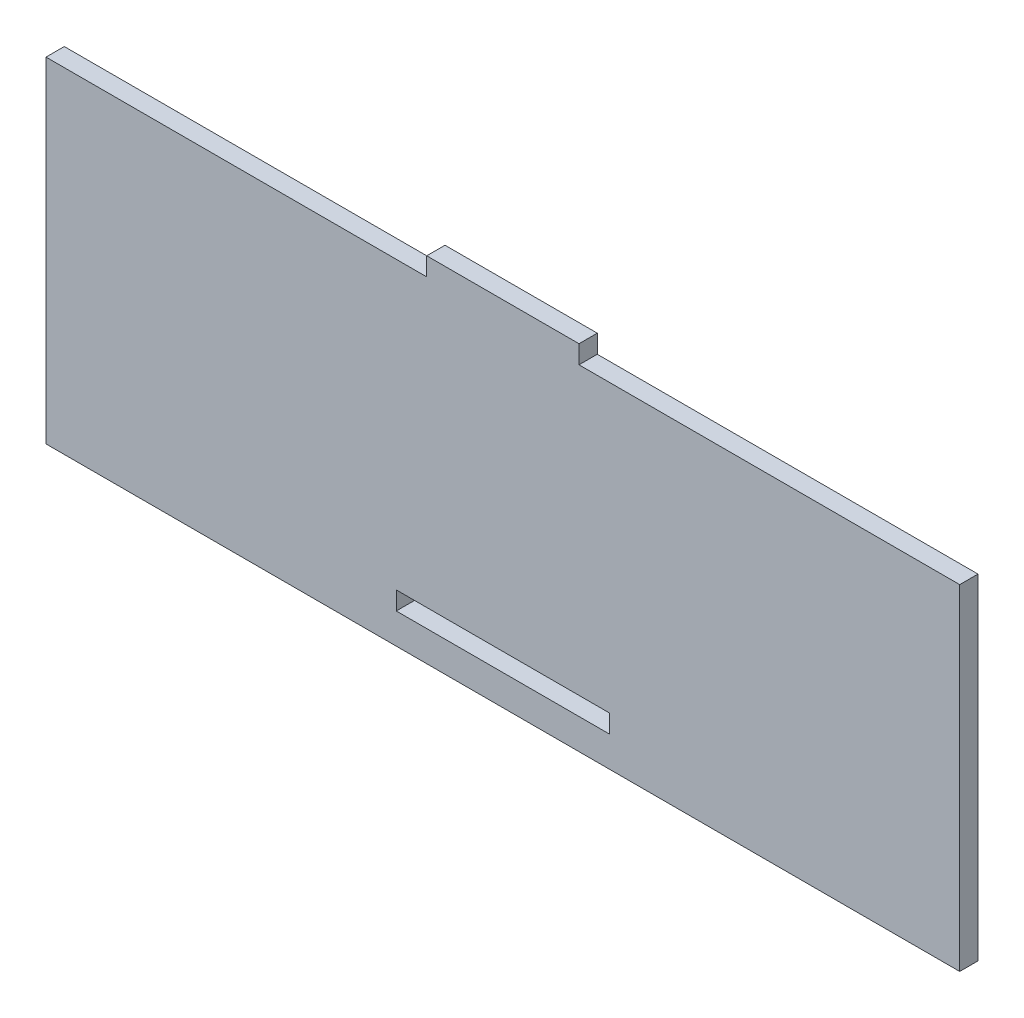
SolidWorks part; units mm, degrees
ref_plane "Спереди" through (0, 0, 0) normal (0, 0, 1) x (1, 0, 0)
ref_plane "Сверху" through (0, 0, 0) normal (0, 1, 0) x (1, 0, 0)
ref_plane "Справа" through (0, 0, 0) normal (1, 0, 0) x (0, 0, -1)
sketch "Эскиз1" plane through (0, 0, 0) normal (0, 0, 1) x (1, 0, 0)
  line L0 (14.2157, 61.3464) -> (76.7157, 61.3464)
  line L1 (-73.2843, 61.3464) -> (-10.7843, 61.3464)
  line L2 (-73.2843, 61.3464) -> (-73.2843, 6.3464)
  line L3 (-73.2843, 6.3464) -> (76.7157, 6.3464)
  line L4 (76.7157, 61.3464) -> (76.7157, 6.3464)
  line L6 (-10.7843, 61.3464) -> (-10.7843, 64.3464)
  line L7 (-10.7843, 64.3464) -> (14.2157, 64.3464)
  line L8 (14.2157, 61.3464) -> (14.2157, 64.3464)
  line L9 (-15.7843, 11.3464) -> (19.2157, 11.3464)
  line L10 (-15.7843, 11.3464) -> (-15.7843, 14.3464)
  line L11 (-15.7843, 14.3464) -> (19.2157, 14.3464)
  line L12 (19.2157, 11.3464) -> (19.2157, 14.3464)
  point P12 (20.9408, 21.4371)
  point P13 (20.1376, 12.2808)
  dimension "D1" = 55
  dimension "D2" = 25
  dimension "D3" = 3
  dimension "D4" = 150
  dimension "D5" = 62.5
  dimension "D6" = 57.5
  dimension "D7" = 35
  dimension "D8" = 3
  dimension "D9" = 5
extrude "Бобышка-Вытянуть1" add sketch "Эскиз1" along normal blind 3
